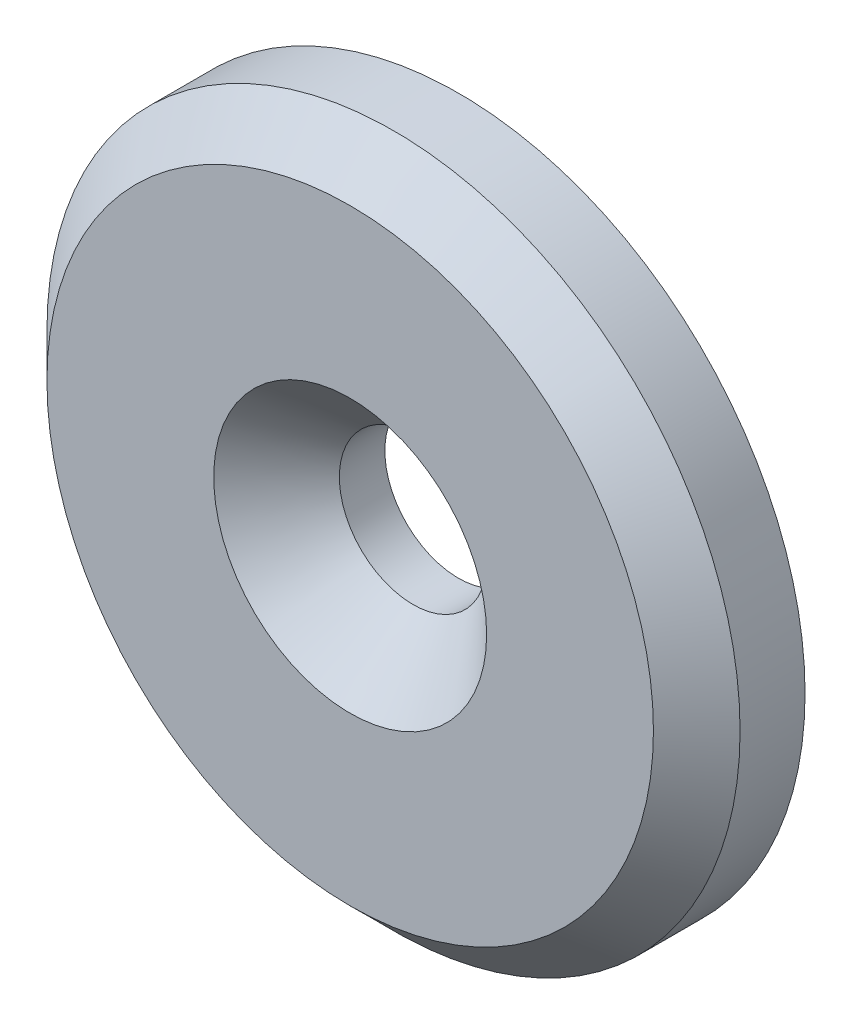
SolidWorks part; units mm, degrees
ref_plane "Спереди" through (0, 0, 0) normal (0, 0, 1) x (1, 0, 0)
ref_plane "Сверху" through (0, 0, 0) normal (0, 1, 0) x (1, 0, 0)
ref_plane "Справа" through (0, 0, 0) normal (1, 0, 0) x (0, 0, -1)
sketch "Эскиз1" plane through (0, 0, 0) normal (0, 0, 1) x (1, 0, 0)
  circle A0 centre (0, 0) radius 8
  dimension "D1" = 16
extrude "Бобышка-Вытянуть1" add sketch "Эскиз1" along normal blind 2.5
chamfer "Фаска1" distance 1 angle 45 1 edges at (8, 0, 2.5)
hole_wizard "Зенковка для винта с полупотайной головкой M31" positions "Эскиз2" profile "Эскиз4" countersink size "M3" standard "ISO" end condition through all
sketch "Эскиз2" plane through (0, 0, 2.5) normal (0, 0, 1) x (1, 0, 0)
  point P0 (0, 0)
sketch "Эскиз4" plane through (0, 0, 2.5) normal (1, 0, 0) x (0, -1, 0)
  line L0 (0, 0) -> (0, 2.5)
  line L1 (0, 2.5) -> (1.7, 2.5)
  line L2 (1.7, 2.5) -> (1.7, 1.45)
  line L3 (1.7, 1.45) -> (3.15, 0)
  line L5 (3.15, 0) -> (0, 0)
  line L6 (-1.7, 1.45) -> (-3.15, 0) construction
  line L11 (0, -6.35) -> (0, 107.95) construction
  dimension "Диаметр сквозного отверстия" = 3.4
  dimension "Глубина сквозного отверстия" = 2.5
  dimension "Диаметр передней зенковки" = 6.3
  dimension "Угол передней зенковки" = 90
